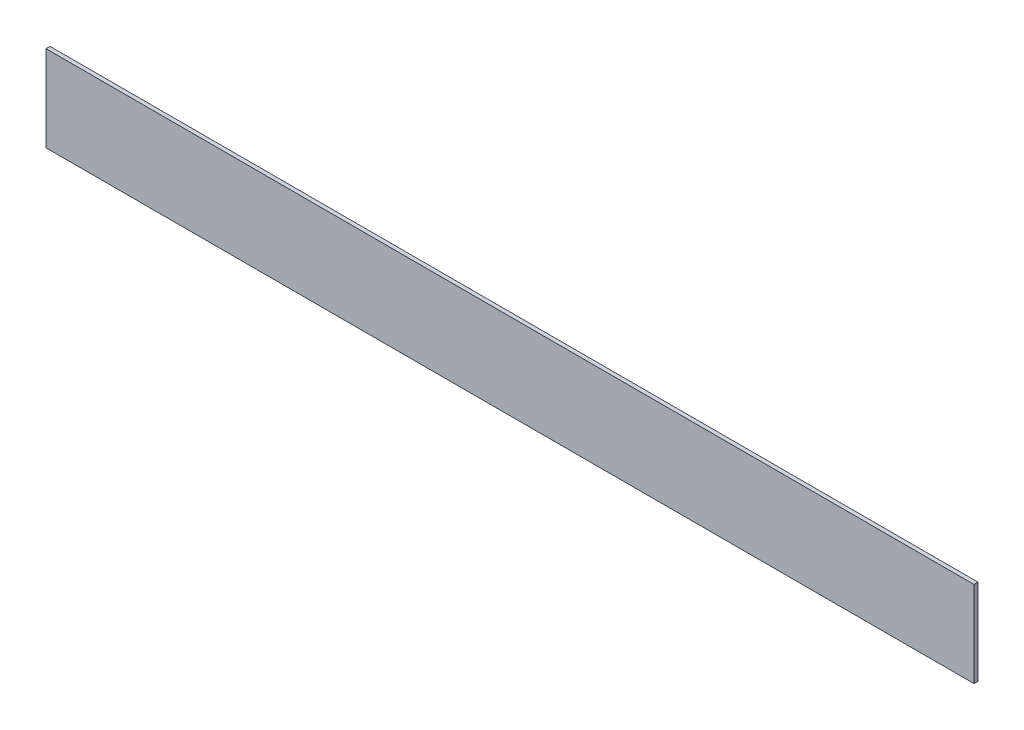
SolidWorks part; units mm, degrees
ref_plane "Спереди" through (0, 0, 0) normal (0, 0, 1) x (1, 0, 0)
ref_plane "Сверху" through (0, 0, 0) normal (0, 1, 0) x (1, 0, 0)
ref_plane "Справа" through (0, 0, 0) normal (1, 0, 0) x (0, 0, -1)
sketch "Эскиз1" plane through (0, 0, 0) normal (0, 0, 1) x (1, 0, 0)
  line L1 (447, -436.3) -> (447, 436.3) construction
  line L2 (-949, -436.3) -> (447, -436.3)
  line L3 (-949, -436.3) -> (-949, -307.08)
  line L4 (-949, -307.08) -> (447, -307.08)
  line L5 (447, -436.3) -> (447, -307.08)
  line L6 (441, -307.08) -> (-943, -307.08) construction
extrude "Бобышка-Вытянуть1" add sketch "Эскиз1" against normal blind 6
equation "\"Ширина груза\"= 420"
equation "\"Глубина груза\"= 490"
equation "\"Высота груза\"= 297"
equation "\"Ширина ячейки\"= \"Ширина груза\" + 10"
equation "\"Глубина ячейки\"= \"Глубина груза\" + 10"
equation "\"Высота ячейки\"= \"Высота груза\" + 10 + 13"
equation "\"Колво ячеек ширина\"= 2"
equation "\"Колво ячеек высота\"= 2"
equation "\"Толщина стенки\" = 6"
equation "\"Крепление дверцы\"= 5"
equation "\"Ширина рейки\"= \"Толщина шестерни\""
equation "\"Высота рейки\"= 20"
equation "\"Высота пола\"= 20"
equation "\"Колво полозьев\"= 5"
equation "\"Отступ рейки\"= 20"
equation "\"Глубина каретки\"= \"Глубина ячейки\" + 30 + \"Мотор Y высота корпуса\" + 20"
equation "\"Длинна рейки\"= ( \"Ширина ячейки\" + \"Толщина стенки\" + \"Крепление дверцы\" ) * \"Колво ячеек ширина\" + \"Ширина ячейки выгрузки\" * \"Колво выгрузки\" + \"Толщина стенки\""
equation "\"Отступ шпильки\"= 26"
equation "\"Диаметр шпильки\"= 5"
equation "\"Длинна шпильки\"= ( \"Высота ячейки\" + \"Толщина стенки\" + \"Высота пола\" ) * \"Колво ячеек высота\" + ( \"Толщина стенки\" + \"Отступ рейки\" ) * 2 "
equation "\"Ширина пластины\"= 50  "
equation "\"Высота зона выгрузки\"= \"Высота ячейки\" * 2 + \"Толщина стенки\" * 2"
equation "\"Колво выгрузки\"= 1"
equation "\"Ширина ячейки выгрузки\"= \"Ширина ячейки\" + \"Толщина стенки\" + \"Отступ крепления мотора фиксации\"*2"
equation "\"Отступ крепления мотора фиксации\" = 30"
equation "\"Мотор X ширина корпуса\"= 42.3"
equation "\"Мотор X высота корпуса\"= 42.3"
equation "\"Мотор X длина корпуса\"= 40"
equation "\"Мотор X вылет вала\"= 19.8"
equation "\"Мотор Y ширина корпуса\"= 42.3"
equation "\"Мотор Y высота корпуса\"= 42.3"
equation "\"Мотор Y длина корпуса\"= 48"
equation "\"Мотор Y вылет вала\"= 30"
equation "\"Мотор Z ширина корпуса\"= 42"
equation "\"Мотор Z высота корпуса\"= 42"
equation "\"Мотор Z длина корпуса\"= 40"
equation "\"Мотор Z вылет вала\"= 23"
equation "\"Мотор диаметр вала ПРЕДВ\"= 5"
equation "\"Мотор шаг крепления ПРЕДВ\"= 31"
equation "\"Мотор диаметр отверстий ПРЕДВ\"= 3"
equation "\"Мотор глубина отверстий ПРЕДВ\"= 4.5"
equation "\"Мотор диаметр буртика ПРЕДВ\"= 22"
equation "\"Мотор высота буртика ПРЕДВ\"= 2"
equation "\"Мотор диаметр шкива ПРЕДВ\"= 16"
equation "\"Мотор длина шкива ПРЕДВ\"= 12"
equation "\"Мотор отступ шкива ПРЕДВ\"= 5"
equation "\"Мотор X шаг градусов\"= 1.8"
equation "\"Мотор Y шаг градусов\"= 1.8"
equation "\"Мотор Z шаг градусов\"= 1.8"
equation "\"Мотор Y диаметр ротора\"= 25.78"
equation "\"Толщина шестерни\"= 10"
equation "\"D1@Бобышка-Вытянуть1\"=\"Толщина стенки\""
